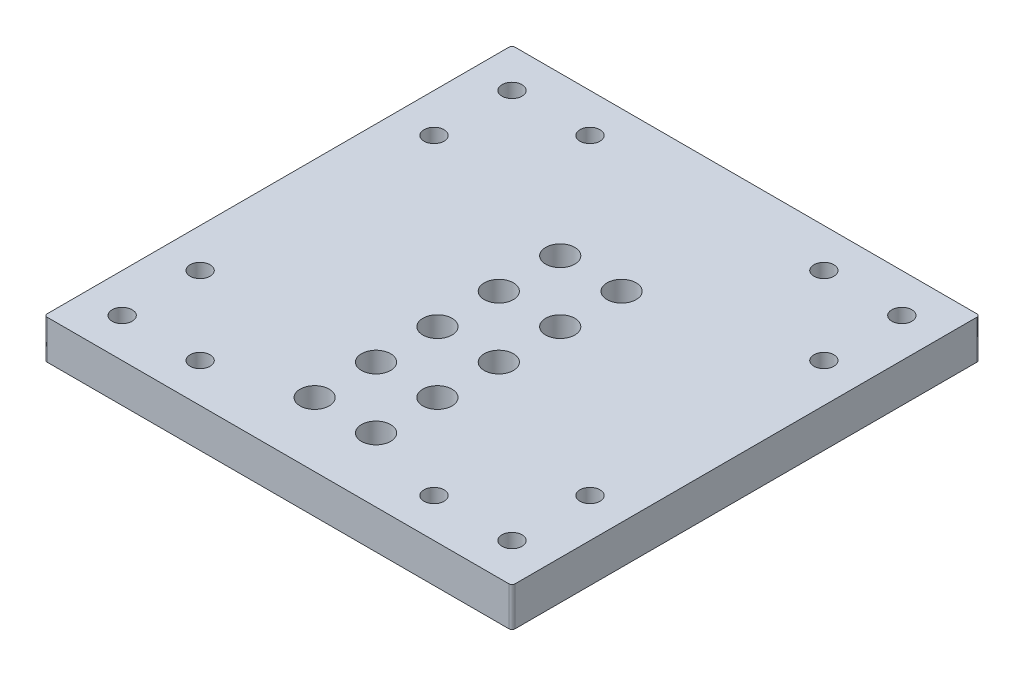
SolidWorks part; units mm, degrees
ref_plane "Front Plane" through (0, 0, 0) normal (0, 0, 1) x (1, 0, 0)
ref_plane "Top Plane" through (0, 0, 0) normal (0, 1, 0) x (1, 0, 0)
ref_plane "Right Plane" through (0, 0, 0) normal (1, 0, 0) x (0, 0, -1)
sketch "Sketch1" plane through (0, 0, 0) normal (0, 1, 0) x (1, 0, 0)
  line L0 (152.4, -76.2) -> (0, -76.2) construction
  line L1 (0, 0) -> (152.4, 0)
  line L2 (0, 0) -> (0, -152.4)
  line L3 (0, -152.4) -> (152.4, -152.4)
  line L4 (152.4, 0) -> (152.4, -152.4)
  line L5 (-6.35, 6.35) -> (158.75, 6.35) construction
  line L6 (-6.35, 6.35) -> (-6.35, -158.75) construction
  line L7 (-6.35, -158.75) -> (158.75, -158.75) construction
  line L8 (158.75, 6.35) -> (158.75, -158.75) construction
  circle A4 centre (12.7, -12.7) radius 4.75
  circle A5 centre (139.7, -12.7) radius 4.75
  circle A6 centre (139.7, -139.7) radius 4.75
  circle A7 centre (12.7, -139.7) radius 4.75
  circle A8 centre (38.1, -12.7) radius 4.75
  circle A9 centre (114.3, -12.7) radius 4.75
  circle A10 centre (139.7, -38.1) radius 4.75
  circle A11 centre (139.7, -114.3) radius 4.75
  circle A12 centre (114.3, -139.7) radius 4.75
  circle A13 centre (38.1, -139.7) radius 4.75
  circle A14 centre (12.7, -114.3) radius 4.75
  circle A15 centre (12.7, -38.1) radius 4.75
  point P5 (12.7, -12.7)
  point P6 (139.7, -12.7)
  point P7 (139.7, -139.7)
  point P8 (12.7, -139.7)
  point P40 (38.1, -12.7)
  point P41 (12.7, -38.1)
  point P42 (139.7, -38.1)
  point P43 (114.3, -12.7)
  point P44 (139.7, -114.3)
  point P45 (114.3, -139.7)
  point P46 (38.1, -139.7)
  point P47 (12.7, -114.3)
  dimension "D7" = 9.5
  dimension "D1" = 127
  dimension "D2" = 127
  dimension "D3" = 12.7
  dimension "D4" = 12.7
  dimension "D5" = 12.7
  dimension "D6" = 12.7
  dimension "D8" = 165.1
  dimension "D10" = 6.35
  dimension "D11" = 152.4
  dimension "D12" = 6.35
  dimension "D13" = 38.1
  dimension "D15" = 38.1
  dimension "D14" = 38.1
  dimension "D16" = 38.1
extrude "Boss-Extrude1" add sketch "Sketch1" along normal blind 12.7 contours L4 L1 L2 L3 A15 A14 A13 A12 A11 A10 A9 A8 A7 A6 A5 A4 | A4 | A5 | A6 | A7 | A8 | A15 | A10 | A9 | A11 | A12 | A14 | A13
ref_plane "Top of Object Plane" through (0, 12.7, 0) normal (0, 1, 0) x (1, 0, 0)
ref_plane "Lower Object Plane" through (0, 6.858, 0) normal (0, 1, 0) x (1, 0, 0)
fillet "Fillet1" radius 1 4 edges at (152.4, 6.35, 152.4) (152.4, 6.35, 0) (0, 6.35, 0) (0, 6.35, 152.4)
sketch "Sketch11" plane through (0, 12.7, 0) normal (0, 1, 0) x (1, 0, 0)
  line L2 (0, -1) -> (0, -151.4) construction
  line L3 (1, 0) -> (151.4, 0) construction
  line L4 (0, -76.2) -> (152.4, -76.2) construction
  line L5 (152.4, -1) -> (152.4, -151.4) construction
  line L6 (76.2, 0) -> (76.2, -152.4) construction
  line L7 (1, -152.4) -> (151.4, -152.4) construction
  circle A0 centre (38.1, -12.7) radius 3.2639
  circle A1 centre (12.7, -12.7) radius 3.2639
  circle A2 centre (139.7, -12.7) radius 3.2639
  circle A3 centre (12.7, -38.1) radius 3.2639
  circle A4 centre (114.3, -12.7) radius 3.2639
  circle A5 centre (139.7, -38.1) radius 3.2639
  circle A6 centre (139.7, -114.3) radius 3.2639
  circle A7 centre (114.3, -139.7) radius 3.2639
  circle A8 centre (12.7, -114.3) radius 3.2639
  circle A9 centre (38.1, -139.7) radius 3.2639
  circle A10 centre (139.7, -139.7) radius 3.2639
  circle A11 centre (12.7, -139.7) radius 3.2639
  point P40 (0, 0)
  point P41 (0, 0)
  dimension "D1" = 38.1
  dimension "D3" = 38.1
  dimension "D4" = 6.5278
  dimension "D2" = 12.7
  dimension "D5" = 12.7
extrude "Cut-Extrude1" cut sketch "Sketch11" against normal up to surface (12.7 mm away) up to face at (76.2, 0, 76.2)
sketch "Sketch12" plane through (0, 0, 0) normal (0, -1, 0) x (1, 0, 0)
  line L0 (67.2, 131.495) -> (87.2, 131.495) construction
  line L1 (1, 152.4) -> (151.4, 152.4) construction
  line L2 (152.4, 1) -> (152.4, 151.4) construction
  circle A0 centre (67.2, 131.495) radius 4.75
  circle A1 centre (87.2, 131.495) radius 4.75
  circle A2 centre (87.2, 111.495) radius 4.75
  circle A3 centre (67.2, 111.495) radius 4.75
  circle A4 centre (67.2, 91.495) radius 4.75
  circle A5 centre (67.2, 71.495) radius 4.75
  circle A6 centre (67.2, 51.495) radius 4.75
  circle A7 centre (87.2, 51.495) radius 4.75
  circle A8 centre (87.2, 71.495) radius 4.75
  circle A9 centre (87.2, 91.495) radius 4.75
  point P0 (67.2, 131.495)
  point P4 (77.2, 131.495)
  point P7 (67.2, 111.495)
  point P8 (67.2, 91.495)
  point P9 (67.2, 71.495)
  point P10 (67.2, 51.495)
  point P11 (87.2, 111.495)
  point P12 (87.2, 91.495)
  point P13 (87.2, 71.495)
  point P14 (87.2, 51.495)
  point P15 (87.2, 131.495)
  dimension "D8" = 9.5
  dimension "D1" = 75.2
  dimension "D2" = 20.905
  dimension "D5" = 20
  dimension "D6" = 20
  dimension "D7" = 80
  dimension "D3" = 5
  dimension "D4" = 2
extrude "Cut-Extrude2" cut sketch "Sketch12" against normal up to surface (12.7 mm away) up to face at (12.7, 12.7, 41.3639)
equation "\"D2@Sketch1\"=\"D1@Sketch1\""
equation "\"D4@Sketch1\"=\"D3@Sketch1\""
equation "\"D5@Sketch1\"=\"D3@Sketch1\""
equation "\"D6@Sketch1\"=\"D5@Sketch1\""
equation "\"D9@Sketch1\"=\"D8@Sketch1\""
equation "\"D12@Sketch1\"=\"D10@Sketch1\""
equation "\"Ball_rest_location\"= 0"
equation "\"D15@Sketch1\"=\"D13@Sketch1\""
equation "\"D14@Sketch1\"=\"D13@Sketch1\""
equation "\"D16@Sketch1\"=\"D13@Sketch1\""
equation "\"Outer_circle_Dia\"= 0"
